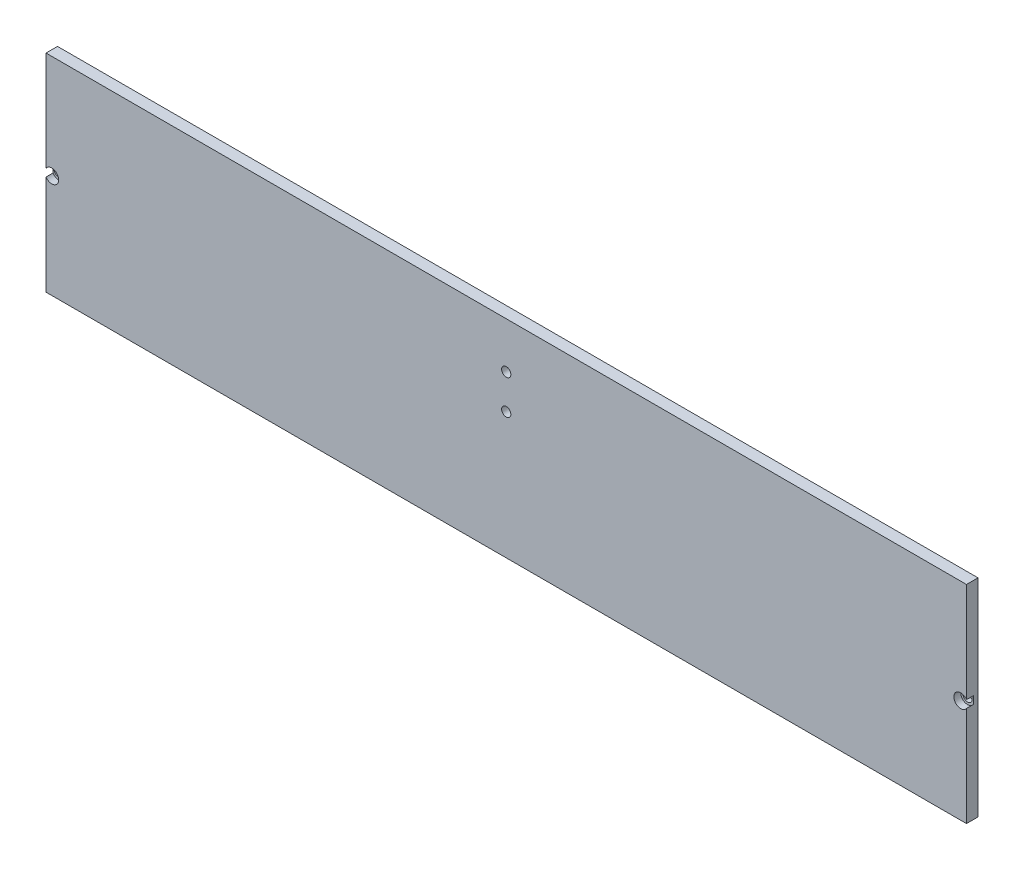
SolidWorks part; units mm, degrees
ref_plane "Front Plane" through (0, 0, 0) normal (0, 0, 1) x (1, 0, 0)
ref_plane "Top Plane" through (0, 0, 0) normal (0, 1, 0) x (1, 0, 0)
ref_plane "Right Plane" through (0, 0, 0) normal (1, 0, 0) x (0, 0, -1)
sketch "Sketch1" plane through (0, 0, 0) normal (0, 0, 1) x (1, 0, 0)
  line L1 (0, 0) -> (400, 0)
  line L2 (0, 0) -> (0, 90)
  line L3 (0, 90) -> (400, 90)
  line L4 (400, 0) -> (400, 90)
  circle A0 centre (2.5, 45) radius 2
  circle A1 centre (397.5, 45) radius 2
  circle A2 centre (200, 55) radius 2
  circle A3 centre (200, 70) radius 2
  dimension "D3" = 35
  dimension "D1" = 90
  dimension "D2" = 400
  dimension "D4" = 20
  dimension "D5" = 200
  dimension "D6" = 200
  dimension "D7" = 2.5
  dimension "D8" = 2.5
  dimension "D9" = 45
  dimension "D10" = 45
extrude "Boss-Extrude2" add sketch "Sketch1" along normal blind 5 contours L2 L1 L4 L3 | A1 | A3 | A2 | A0
sketch "Sketch2" plane through (0, 0, 5) normal (0, 0, 1) x (1, 0, 0)
  circle A0 centre (2.5, 45) radius 3
  circle A1 centre (397.5, 45) radius 3
extrude "Cut-Extrude1" cut sketch "Sketch2" against normal blind 3 contours A0 | A1
sketch "Sketch3" plane through (0, 0, 0) normal (0, -1, 0) x (1, 0, 0)
  line L0 (0, 5) -> (400, 5) construction
  line L1 (0, 5) -> (0, 0) construction
  line L2 (400, 5) -> (400, 0) construction
  circle A0 centre (40, 2.5) radius 1.25
  circle A1 centre (360, 2.5) radius 1.25
  dimension "D1" = 2.5
  dimension "D3" = 40
  dimension "D2" = 40
  dimension "D4" = 2.5
extrude "Cut-Extrude2" cut sketch "Sketch3" against normal blind 15
